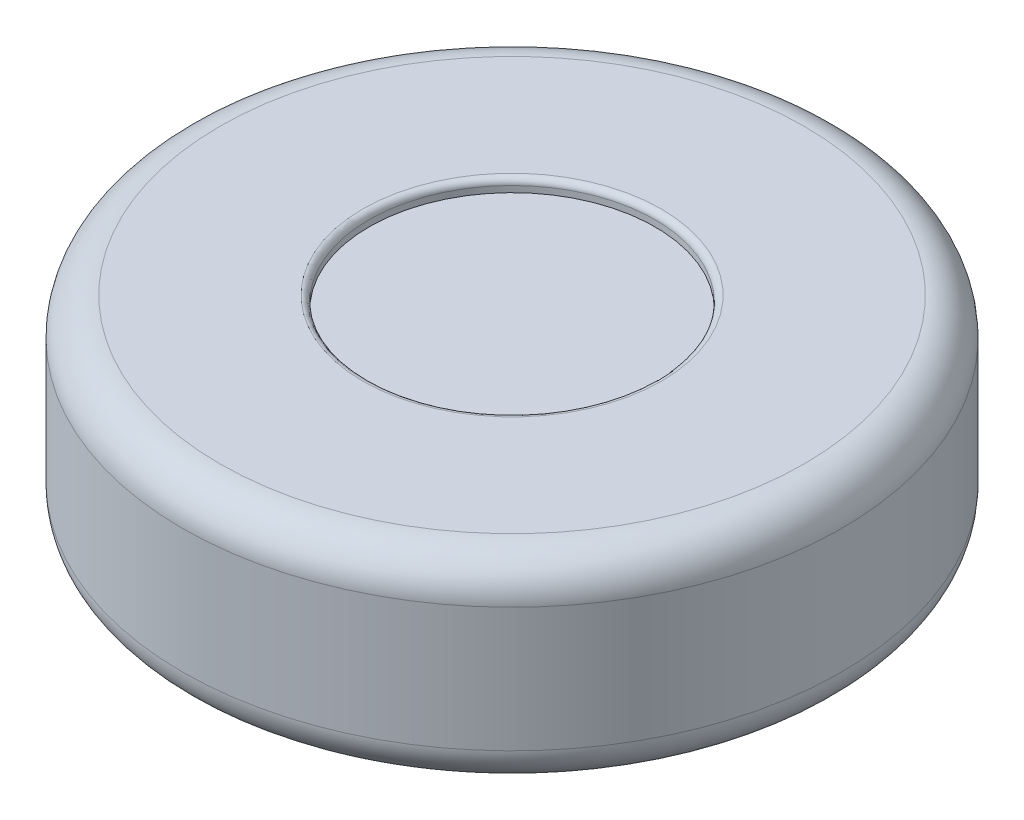
SolidWorks part; units mm, degrees
ref_plane "Alzado" through (0, 0, 0) normal (0, 0, 1) x (1, 0, 0)
ref_plane "Planta" through (0, 0, 0) normal (0, 1, 0) x (1, 0, 0)
ref_plane "Vista lateral" through (0, 0, 0) normal (1, 0, 0) x (0, 0, -1)
sketch "Croquis1" plane through (0, 0, 0) normal (0, 1, 0) x (1, 0, 0)
  circle A0 centre (0, 0) radius 115
  dimension "D1" = 230
extrude "Saliente-Extruir1" add sketch "Croquis1" along normal blind 140
ref_plane "Plano1" through (0, 70, 0) normal (0, 1, 0) x (1, 0, 0)
sketch "Croquis2" plane through (0, 70, 0) normal (0, 1, 0) x (1, 0, 0)
  circle A0 centre (0, 0) radius 115
  circle A1 centre (0, 0) radius 265
  dimension "D1" = 230
  dimension "D2" = 530
extrude "Saliente-Extruir2" add sketch "Croquis2" along normal blind 80 and the other way blind 80
fillet "Redondeo1" radius 30 2 edges at (0, 150, 265) (0, -10, 265)
fillet "Redondeo2" radius 5 1 edges at (0, -10, 115)
fillet "Redondeo3" radius 5 1 edges at (0, 150, 115)
